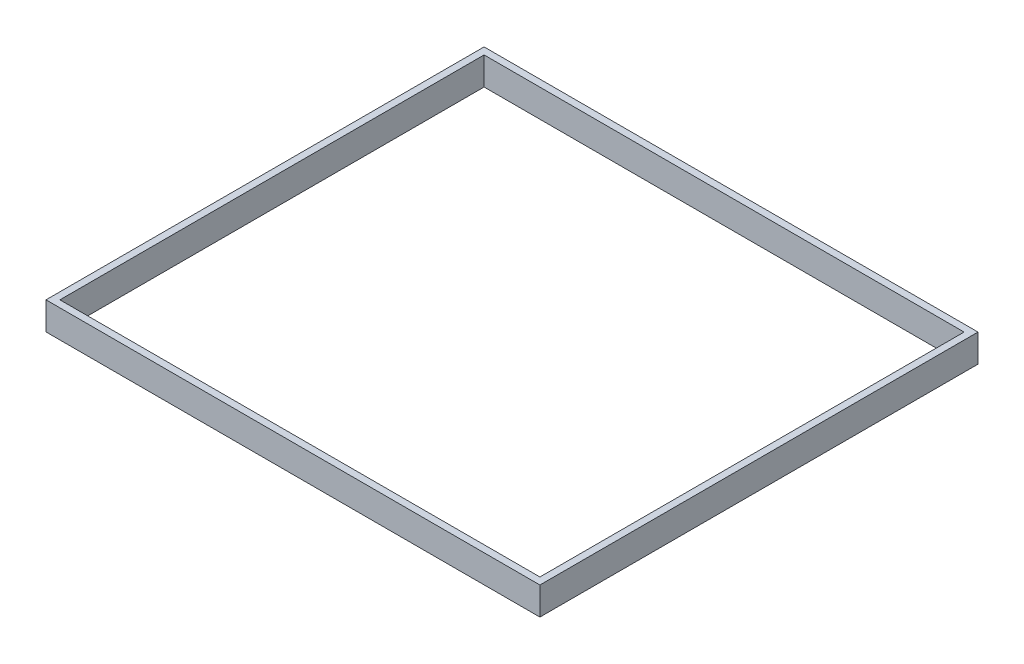
SolidWorks part; units mm, degrees
ref_plane "Front Plane" through (0, 0, 0) normal (0, 0, 1) x (1, 0, 0)
ref_plane "Top Plane" through (0, 0, 0) normal (0, 1, 0) x (1, 0, 0)
ref_plane "Right Plane" through (0, 0, 0) normal (1, 0, 0) x (0, 0, -1)
sketch "Sketch1" plane through (0, 0, 0) normal (0, 1, 0) x (1, 0, 0)
  line L1 (-138.037, 121.9862) -> (138.037, 121.9862)
  line L2 (-138.037, 121.9862) -> (-138.037, -121.9862)
  line L3 (-138.037, -121.9862) -> (138.037, -121.9862)
  line L4 (138.037, 121.9862) -> (138.037, -121.9862)
  line L5 (0, -121.9862) -> (0, 121.9862) construction
  line L6 (-138.037, 0) -> (138.037, 0) construction
  point P0 (0, 0)
extrude "Extrude-Thin1" add sketch "Sketch1" along normal blind 16 thin thin type one direction wall 4
